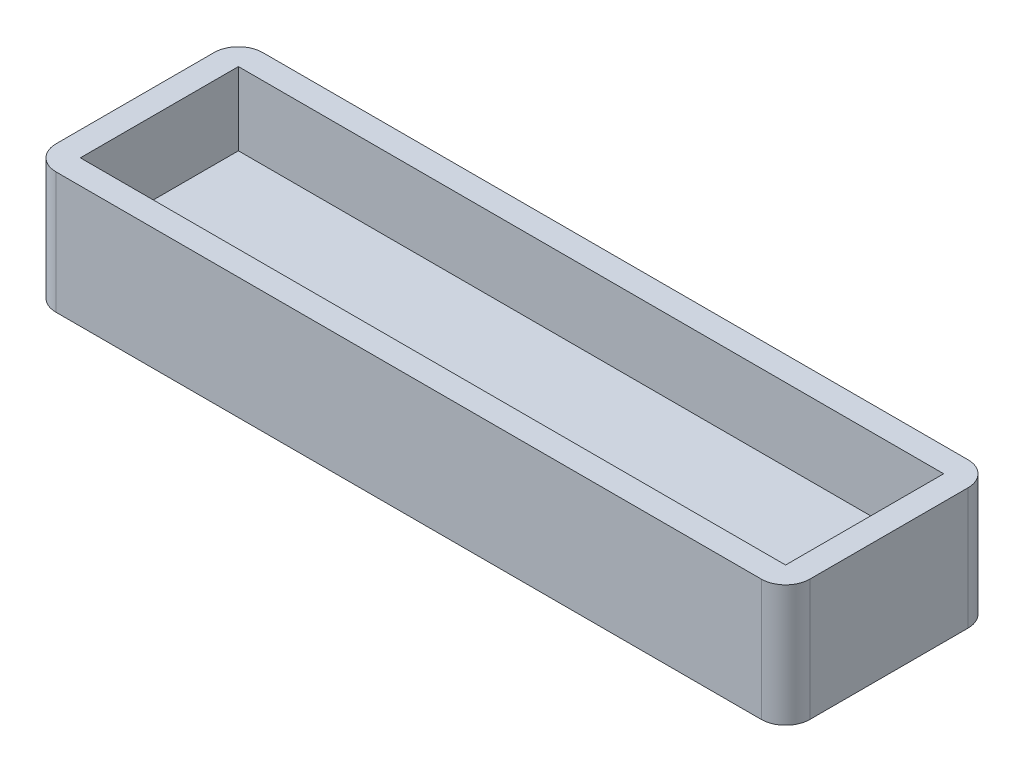
SolidWorks part; units mm, degrees
ref_plane "Ebene vorne" through (0, 0, 0) normal (0, 0, 1) x (1, 0, 0)
ref_plane "Ebene oben" through (0, 0, 0) normal (0, 1, 0) x (1, 0, 0)
ref_plane "Ebene rechts" through (0, 0, 0) normal (1, 0, 0) x (0, 0, -1)
sketch "Skizze2" plane through (0, 0, 0) normal (0, 0, 1) x (1, 0, 0)
  line L1 (0, 0) -> (310, 0)
  line L2 (0, 0) -> (0, 50)
  line L3 (0, 50) -> (310, 50)
  line L4 (310, 0) -> (310, 50)
  dimension "D1" = 310
  dimension "D2" = 50
extrude "Aufsatz-Linear austragen1" add sketch "Skizze2" along normal blind 85
sketch "Skizze4" plane through (0, 50, 0) normal (0, 1, 0) x (1, 0, 0)
  line L0 (310, 0) -> (0, 0) construction
  line L1 (10, -10) -> (300, -10)
  line L2 (10, -10) -> (10, -75)
  line L3 (10, -75) -> (300, -75)
  line L4 (300, -10) -> (300, -75)
  line L5 (310, -85) -> (0, -85) construction
  line L6 (0, -85) -> (0, 0) construction
  line L7 (310, -85) -> (310, 0) construction
  dimension "D1" = 10
  dimension "D2" = 10
  dimension "D3" = 10
  dimension "D4" = 10
extrude "Schnitt-Linear austragen1" cut sketch "Skizze4" against normal blind 30
fillet "Verrundung1" radius 10 1 edges at (310, 25, 0)
fillet "Verrundung2" radius 10 1 edges at (310, 25, 85)
fillet "Verrundung3" radius 10 1 edges at (0, 25, 85)
fillet "Verrundung4" radius 10 1 edges at (0, 25, 0)
sketch "Skizze9" plane through (0, 0, 0) normal (0, 0, -1) x (-1, 0, 0)
  line L1 (-290, 29) -> (-282, 29)
  line L2 (-290, 29) -> (-290, 25)
  line L3 (-290, 25) -> (-282, 25)
  line L4 (-282, 29) -> (-282, 25)
  line L5 (-10, 0) -> (-300, 0) construction
  line L6 (-300, 50) -> (-300, 0) construction
  dimension "D1" = 4
  dimension "D2" = 8
  dimension "D3" = 25
  dimension "D4" = 10
extrude "Schnitt-Linear austragen2" cut sketch "Skizze9" against normal blind 10
sketch "Skizze10" plane through (0, 20, 0) normal (0, 1, 0) x (1, 0, 0)
  line L0 (300, -75) -> (300, -10) construction
  line L1 (300, -10) -> (10, -10) construction
  line L2 (10, -75) -> (300, -75) construction
  circle A0 centre (286, -15) radius 1.5
  circle A1 centre (286, -70) radius 1.5
  dimension "D1" = 3
  dimension "D2" = 14
  dimension "D4" = 3
  dimension "D3" = 5
  dimension "D5" = 5
extrude "Schnitt-Linear austragen3" cut sketch "Skizze10" against normal blind 6
